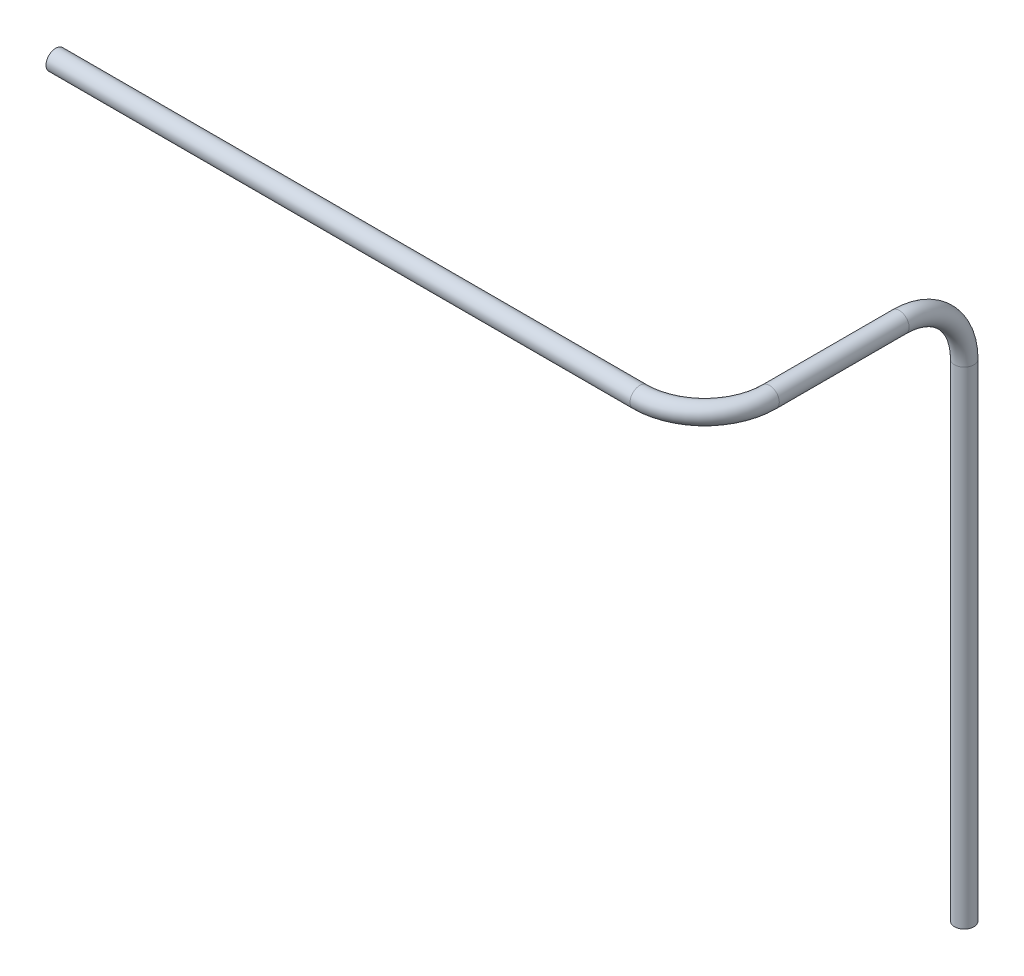
SolidWorks part; units mm, degrees
ref_plane "Plan de face" through (0, 0, 0) normal (0, 0, 1) x (1, 0, 0)
ref_plane "Plan de dessus" through (0, 0, 0) normal (0, 1, 0) x (1, 0, 0)
ref_plane "Plan de droite" through (0, 0, 0) normal (1, 0, 0) x (0, 0, -1)
sketch3d "Esquisse3D1"
  line L0 (0, 0, 0) -> (0, 150, 0)
  line L1 (0, 170, 20) -> (0, 170, 60)
  line L2 (-20, 170, 80) -> (-200, 170, 80)
  arc A0 (0, 150, 0) -> (0, 170, 20) centre (0, 150, 20) ccw
  arc A1 (0, 170, 60) -> (-20, 170, 80) centre (-20, 170, 60) ccw
  point P7 (0, 170, 0)
  point P8 (20, 150, 20)
  point P11 (0, 170, 80)
  point P12 (-20, 150, 60)
  dimension "D1" = 20
sketch "Esquisse2" plane through (0, 0, 0) normal (0, 1, 0) x (1, 0, 0)
  circle A0 centre (0, 0) radius 2
  circle A1 centre (0, 0) radius 3
sweep "Balayage1" add profiles "Esquisse2" path "Esquisse3D1"
